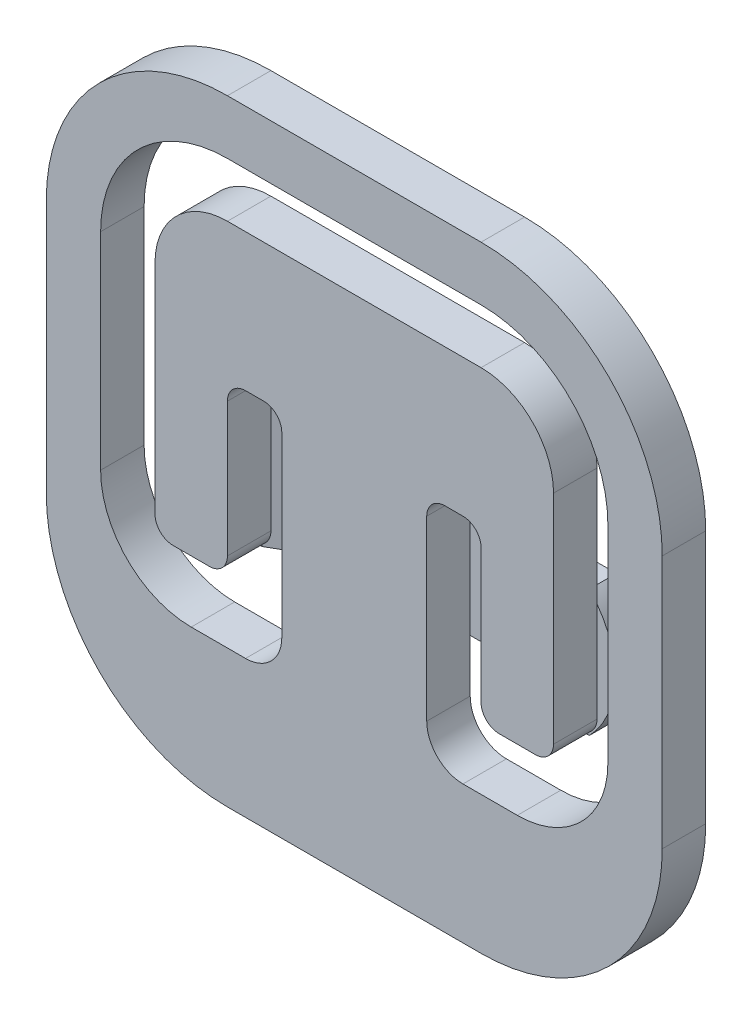
SolidWorks part; units mm, degrees
ref_plane "Front Plane" through (0, 0, 0) normal (0, 0, 1) x (1, 0, 0)
ref_plane "Top Plane" through (0, 0, 0) normal (0, 1, 0) x (1, 0, 0)
ref_plane "Right Plane" through (0, 0, 0) normal (1, 0, 0) x (0, 0, -1)
sketch "Sketch1" plane through (0, 0, 0) normal (0, 0, 1) x (1, 0, 0)
  line L0 (-14, 7) -> (-14, -4.4)
  line L1 (-7, 17) -> (7, 17)
  line L2 (-17, 7) -> (-17, -7)
  line L3 (-7, -17) -> (7, -17)
  line L5 (-17, 17) -> (17, -17) construction
  line L6 (-17, -17) -> (17, 17) construction
  line L9 (-7, 14) -> (7, 14)
  line L10 (-9, -9.4) -> (-6, -9.4)
  line L13 (-14, 7) -> (-14, -7) construction
  line L14 (14, 7) -> (14, -7) construction
  line L15 (0, -1034) -> (0, -17) construction
  line L16 (-7, 11) -> (7, 11)
  line L17 (-7, 11) -> (0, 11)
  line L18 (-4, 2.4) -> (-4, -7.4)
  line L21 (0, 17) -> (0, 50000) construction
  line L24 (-8, -6) -> (-10, -6)
  line L25 (-11, 7) -> (-11, -5)
  line L26 (-7, -5) -> (-7, 2.4)
  line L27 (-6, 3.4) -> (-5, 3.4)
  line L29 (-7, -14) -> (7, -14) construction
  line L30 (-7, 17) -> (7, 17) construction
  line L31 (-7, 14) -> (7, 14) construction
  line L32 (0, -18.7) -> (0, 18.7) construction
  line L33 (-7, 11) -> (7, 11) construction
  line L34 (-7, -17) -> (7, -17) construction
  line L35 (17, 7) -> (17, -7) construction
  line L36 (17, 7) -> (17, -7)
  line L37 (9, -9.4) -> (6, -9.4)
  line L38 (8, -6) -> (10, -6)
  line L39 (7, -5) -> (7, 2.4)
  line L40 (6, 3.4) -> (5, 3.4)
  line L41 (4, 2.4) -> (4, -7.4)
  line L42 (11, 7) -> (11, -5)
  line L43 (14, 7) -> (14, -4.4)
  arc A2 (-17, -7) -> (-7, -17) centre (-7, -7) ccw
  arc A3 (-7, 17) -> (-17, 7) centre (-7, 7) ccw
  arc A7 (-7, 14) -> (-14, 7) centre (-7, 7) ccw
  arc A8 (-14, -7) -> (-7, -14) centre (-7, -7) ccw construction
  arc A9 (7, -14) -> (14, -7) centre (7, -7) ccw construction
  arc A10 (-9, -9.4) -> (-14, -4.4) centre (-9, -4.4) cw
  arc A12 (17, -7) -> (7, -17) centre (7, -7) cw
  arc A13 (-7, 11) -> (-11, 7) centre (-7, 7) ccw
  arc A15 (-6, -9.4) -> (-4, -7.4) centre (-6, -7.4) ccw
  arc A16 (-4, 2.4) -> (-5, 3.4) centre (-5, 2.4) ccw
  arc A17 (-6, 3.4) -> (-7, 2.4) centre (-6, 2.4) ccw
  arc A18 (-10, -6) -> (-11, -5) centre (-10, -5) cw
  arc A19 (-8, -6) -> (-7, -5) centre (-8, -5) ccw
  arc A20 (7, -17) -> (17, -7) centre (7, -7) ccw construction
  arc A21 (7, 11) -> (11, 7) centre (7, 7) cw construction
  arc A22 (7, 14) -> (14, 7) centre (7, 7) cw construction
  arc A23 (7, 17) -> (17, 7) centre (7, 7) cw construction
  arc A24 (7, 17) -> (17, 7) centre (7, 7) cw
  arc A25 (9, -9.4) -> (14, -4.4) centre (9, -4.4) ccw
  arc A26 (6, -9.4) -> (4, -7.4) centre (6, -7.4) cw
  arc A27 (10, -6) -> (11, -5) centre (10, -5) ccw
  arc A28 (8, -6) -> (7, -5) centre (8, -5) cw
  arc A29 (6, 3.4) -> (7, 2.4) centre (6, 2.4) cw
  arc A30 (4, 2.4) -> (5, 3.4) centre (5, 2.4) cw
  arc A31 (7, 11) -> (11, 7) centre (7, 7) cw
  arc A32 (7, 14) -> (14, 7) centre (7, 7) cw
  point P0 (0, 0)
  point P31 (-5.5, 3.4)
  point P64 (-7, 3.4)
  point P67 (-11, -6)
  point P70 (-7, -6)
  point P101 (0, 14)
  dimension "D2" = 20.4
  dimension "D5" = 5
  dimension "D7" = 4
  dimension "D12" = 1
  dimension "D14" = 1
  dimension "D13" = 2
  dimension "D15" = 7
  dimension "D1" = 34
  dimension "D4" = 23.4
  dimension "D6" = 9.4
  dimension "D9" = 17
  dimension "D10" = 3
  dimension "D11" = 7.6
  dimension "D16" = 10
  dimension "D3" = 3
  dimension "D8" = 3
extrude "Boss-Extrude2" add sketch "Sketch1" along normal mid plane 2.4 contours A24 L1 A3 L2 A2 L3 A12 L36 L9 A32 L43 A25 L37 A26 L41 A30 L40 A29 L39 A28 L38 A27 L42 A31 L16 A13 L25 A18 L24 A19 L26 A17 L27 A16 L18 A15 L10 A10 L0 A7
sketch "Sketch2" plane through (0, 0, -1.2) normal (0, 0, -1) x (-1, 0, 0)
  line L0 (-7, -2.5) -> (7, -2.5) construction
  line L3 (-10.5707, -6) -> (10.5707, -6)
  line L4 (-7, -5) -> (-7, 2.4) construction
  line L5 (7, -5) -> (7, 2.4) construction
  line L6 (-10.5707, 1) -> (10.5707, 1)
  arc A0 (-10.5707, 1) -> (-10.5707, -6) centre (-7, -2.5) ccw
  arc A1 (10.5707, -6) -> (10.5707, 1) centre (7, -2.5) ccw
  point P2 (0, -2.5)
  dimension "D2" = 5
  dimension "D4" = 5
  dimension "D1" = 2.5
extrude "Boss-Extrude3" add sketch "Sketch2" along normal blind 5
sketch "Sketch3" plane through (0, 0, 0) normal (0, 1, 0) x (1, 0, 0)
  line L0 (-4.9019, 4.2) -> (-7.5, 2.7)
  line L1 (-10.5707, 6.2) -> (10.5707, 6.2) construction
  line L2 (-7.5, 2.7) -> (-12, 2.7)
  line L3 (-12, 6.2) -> (-12, 1.2) construction
  line L4 (-10.5707, 1.2) -> (-7, 1.2) construction
  line L6 (4.9019, 2.7) -> (-4.9019, 2.7)
  line L7 (-4.9019, 2.7) -> (-7.5, 1.2)
  line L9 (-7, 1.2) -> (-17, 1.2) construction
  line L11 (0, -4.07) -> (0, 4.07) construction
  line L14 (4.9019, 2.7) -> (7.5, 1.2)
  line L15 (7.5, 2.7) -> (12, 2.7)
  line L16 (4.9019, 4.2) -> (7.5, 2.7)
  line L17 (-7.5, 1.2) -> (7.5, 1.2)
  line L18 (-12, 2.7) -> (-15.9055, 2.7)
  line L19 (-15.9055, 2.7) -> (-15.9055, 4.2)
  line L20 (-4.9019, 4.2) -> (4.9019, 4.2)
  line L21 (14.6106, 4.2) -> (14.6106, 2.7)
  line L22 (14.6106, 2.7) -> (12, 2.7)
  line L23 (14.6106, 4.2) -> (14.6106, 10.094)
  line L24 (14.6106, 10.094) -> (-15.9055, 10.094)
  line L25 (-15.9055, 10.094) -> (-15.9055, 4.2)
  point P23 (0, 2.7)
  point P24 (0, 6.2)
  dimension "D1" = 1.5
  dimension "D2" = 150
  dimension "D3" = 4.5
  dimension "D4" = 1.5
extrude "Cut-Extrude1" cut sketch "Sketch3" against normal through all both and the other way through all contours L7 L6 L14 L17 | L15 L22 L21 L23 L24 L25 L19 L18 L2 L0 L20 L16
ref_plane "Plane1" through (0, -2.5, 0) normal (0, 1, 0) x (1, 0, 0)
sketch "Sketch4" plane through (0, -2.5, 0) normal (0, 1, 0) x (1, 0, 0)
  line L0 (4.9019, 4.2) -> (-4.9019, 4.2) construction
  line L1 (-2.5, 4.2) -> (2.5, 4.2)
  line L2 (0, 0) -> (0, -50000) construction
  arc A0 (2.5, 4.2) -> (-2.5, 4.2) centre (0, -0.3548) ccw
  point P5 (-2.5, 4.2)
  dimension "D1" = 2.5
  dimension "D2" = 0.3548
